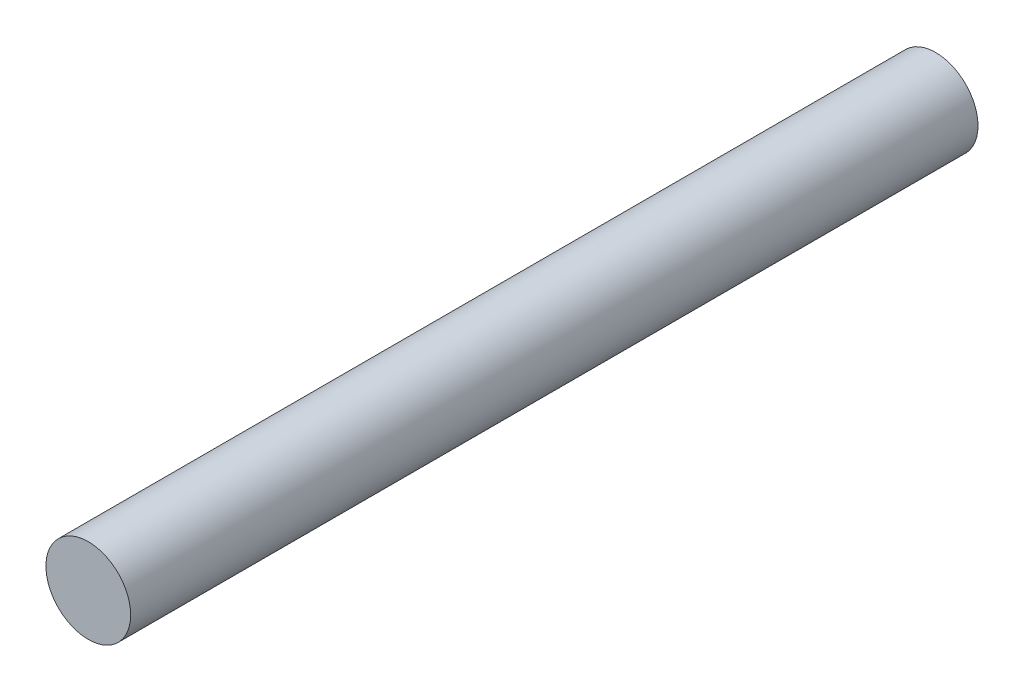
SolidWorks part; units mm, degrees
ref_plane "前视基准面" through (0, 0, 0) normal (0, 0, 1) x (1, 0, 0)
ref_plane "上视基准面" through (0, 0, 0) normal (0, 1, 0) x (1, 0, 0)
ref_plane "右视基准面" through (0, 0, 0) normal (1, 0, 0) x (0, 0, -1)
other "Configuration Table"
sketch "草图1" plane through (0, 0, 0) normal (0, 0, 1) x (1, 0, 0)
  circle A0 centre (0, 0) radius 1
  dimension "D1" = 2
extrude "凸台-拉伸1" add sketch "草图1" along normal blind 20
